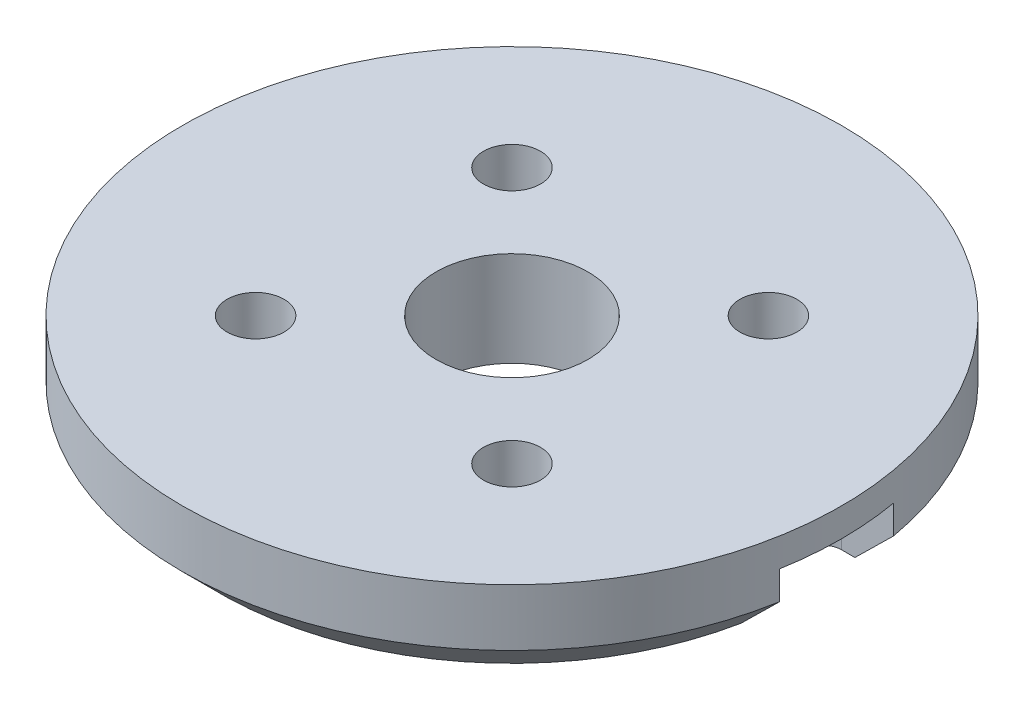
SolidWorks part; units mm, degrees
material "AA380.0-F 锻模"
ref_plane "前视基准面" through (0, 0, 0) normal (0, 0, 1) x (1, 0, 0)
ref_plane "上视基准面" through (0, 0, 0) normal (0, 1, 0) x (1, 0, 0)
ref_plane "右视基准面" through (0, 0, 0) normal (1, 0, 0) x (0, 0, -1)
sketch "草图1" plane through (0, 0, 0) normal (0, 1, 0) x (1, 0, 0)
  circle A0 centre (0, 0) radius 17.35
  dimension "D1" = 34.7
extrude "凸台-拉伸1" add sketch "草图1" along normal blind 5 contours A0
chamfer "倒角1" distance 2 angle 45 1 edges at (0, 0, 17.35)
sketch "草图2" plane through (0, 5, 0) normal (0, 1, 0) x (1, 0, 0)
  circle A0 centre (0, 0) radius 4
  dimension "D1" = 8
extrude "切除-拉伸1" cut sketch "草图2" against normal blind 5
sketch "草图3" plane through (0, 0, 0) normal (0, -1, 0) x (1, 0, 0)
  line L1 (-6.75, 6.75) -> (6.75, 6.75)
  line L2 (-6.75, 6.75) -> (-6.75, -6.75)
  line L3 (-6.75, -6.75) -> (6.75, -6.75)
  line L4 (6.75, 6.75) -> (6.75, -6.75)
  line L5 (-6.75, 6.75) -> (6.75, -6.75) construction
  line L6 (-6.75, -6.75) -> (6.75, 6.75) construction
  circle A0 centre (-6.75, 6.75) radius 1.5
  circle A1 centre (6.75, 6.75) radius 1.5
  circle A2 centre (6.75, -6.75) radius 1.5
  circle A3 centre (-6.75, -6.75) radius 1.5
  point P0 (0, 0)
  point P16 (0, 0)
  dimension "D3" = 3
  dimension "D1" = 13.5
  dimension "D2" = 13.5
  dimension "D4" = 4
extrude "切除-拉伸2" cut sketch "草图3" against normal blind 5 contours A0 | A1 | A3 | A2
sketch "草图4" plane through (0, 0, 0) normal (0, -1, 0) x (1, 0, 0)
  line L0 (0, 0) -> (17.35, 0) construction
  line L2 (14.35, 3) -> (21.35, 3)
  line L3 (13.35, 2) -> (13.35, -2)
  line L4 (14.35, -3) -> (21.35, -3)
  line L5 (21.35, 3) -> (21.35, -3)
  line L6 (13.35, 3) -> (21.35, -3) construction
  line L7 (13.35, -3) -> (21.35, 3) construction
  circle A0 centre (0, 0) radius 17.35 construction
  arc A1 (13.35, -2) -> (14.35, -3) centre (14.35, -2) ccw
  arc A2 (14.35, 3) -> (13.35, 2) centre (14.35, 2) ccw
  dimension "D3" = 1
  dimension "D1" = 6
  dimension "D2" = 8
extrude "切除-拉伸3" cut sketch "草图4" against normal blind 3.5
